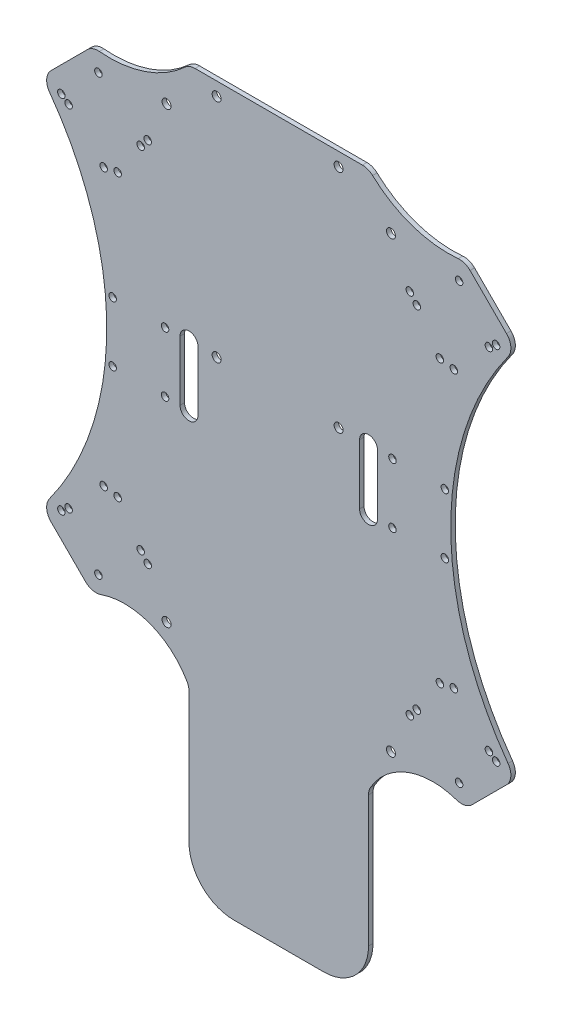
SolidWorks part; units mm, degrees
ref_plane "Front Plane" through (0, 0, 0) normal (0, 0, 1) x (1, 0, 0)
ref_plane "Top Plane" through (0, 0, 0) normal (0, 1, 0) x (1, 0, 0)
ref_plane "Right Plane" through (0, 0, 0) normal (1, 0, 0) x (0, 0, -1)
sketch "Sketch2" plane through (0, 0, 0) normal (0, 0, 1) x (1, 0, 0)
  line L0 (0, 0) -> (0, 50000) construction
  line L1 (0, 0) -> (35355.3391, 35355.3391) construction
  line L2 (0, 0) -> (35355.3391, -35355.3391) construction
  line L3 (-79.196, 62.2254) -> (-62.2254, 79.196)
  line L4 (0, 0) -> (-50000, 0) construction
  line L5 (-79.196, -62.2254) -> (-62.2254, -79.196)
  line L6 (30, 90) -> (-30, 90)
  line L7 (30, -90) -> (30, -135)
  line L8 (79.196, -62.2254) -> (62.2254, -79.196)
  line L9 (-30, -90) -> (-30, -135)
  line L10 (-15, -150) -> (15, -150)
  line L11 (79.196, 62.2254) -> (62.2254, 79.196)
  line L12 (-30, -90) -> (30, -150) construction
  line L13 (-30, -150) -> (30, -90) construction
  line L14 (30, -10) -> (30, 10) construction
  line L15 (27, -10) -> (27, 10)
  line L16 (33, -10) -> (33, 10)
  line L17 (-30, -10) -> (-30, 10) construction
  line L18 (-27, -10) -> (-27, 10)
  line L19 (-33, -10) -> (-33, 10)
  arc A0 (-79.196, 62.2254) -> (-79.196, -62.2254) centre (-157.4775, 0) cw
  arc A1 (-62.2254, 79.196) -> (-30, 90) centre (-56.6326, 115.976) ccw
  arc A2 (-62.2254, -79.196) -> (-30, -90) centre (-51.5147, -100.7107) cw
  arc A3 (15, -150) -> (30, -135) centre (15, -135) ccw
  arc A4 (-15, -150) -> (-30, -135) centre (-15, -135) cw
  arc A5 (62.2254, -79.196) -> (30, -90) centre (51.5147, -100.7107) ccw
  arc A6 (79.196, 62.2254) -> (79.196, -62.2254) centre (157.4775, 0) ccw
  arc A7 (62.2254, 79.196) -> (30, 90) centre (56.6326, 115.976) cw
  circle A8 centre (-37.5, 75) radius 1.5
  circle A9 centre (37.5, 75) radius 1.5
  circle A10 centre (37.5, -75) radius 1.5
  circle A11 centre (-37.5, -75) radius 1.5
  arc A12 (27, -10) -> (33, -10) centre (30, -10) ccw
  arc A13 (33, 10) -> (27, 10) centre (30, 10) ccw
  arc A14 (-27, -10) -> (-33, -10) centre (-30, -10) cw
  arc A15 (-33, 10) -> (-27, 10) centre (-30, 10) cw
  circle A16 centre (-55.5, 10) radius 1.25
  circle A17 centre (-38, 10) radius 1.25
  circle A18 centre (-55.5, -10) radius 1.25
  circle A19 centre (-38, -10) radius 1.25
  circle A20 centre (55.5, -10) radius 1.25
  circle A21 centre (38, -10) radius 1.25
  circle A22 centre (38, 10) radius 1.25
  circle A23 centre (55.5, 10) radius 1.25
  point P16 (-70.7107, 70.7107)
  point P24 (0, -120)
  point P32 (0, -150)
  point P45 (0, 90)
  point P49 (30, 0)
  point P56 (-30, 0)
  dimension "D9" = 10
  dimension "D4" = 37.5
  dimension "D8" = 30
  dimension "D17" = 2.5
  dimension "D1" = 150
  dimension "D2" = 45
  dimension "D3" = 45
  dimension "D5" = 30
  dimension "D6" = 60
  dimension "D7" = 75
  dimension "D10" = 10
  dimension "D11" = 10
  dimension "D12" = 10
  dimension "D13" = 17.5
  dimension "D14" = 17.5
  dimension "D15" = 38
  dimension "D16" = 38
extrude "Boss-Extrude1" add sketch "Sketch2" along normal blind 1.5
sketch "Sketch3" plane through (0, 0, 1.5) normal (0, 0, 1) x (1, 0, 0)
  line L0 (-70.7107, 70.7107) -> (35284.6284, -35284.6284) construction
  line L1 (-79.196, 62.2254) -> (-62.2254, 79.196) construction
  line L2 (0, 90) -> (0, 50090) construction
  line L3 (30, 90) -> (-30, 90) construction
  line L4 (70.7107, 70.7107) -> (35426.0497, 35426.0497) construction
  line L5 (79.196, 62.2254) -> (62.2254, 79.196) construction
  line L6 (0, 0) -> (50000, 0) construction
  circle A0 centre (-72.6552, 60.2809) radius 1.25
  circle A1 centre (-58.5131, 46.1387) radius 1.25
  circle A2 centre (-60.2809, 72.6552) radius 1.25
  circle A3 centre (-46.1387, 58.5131) radius 1.25
  circle A4 centre (58.5131, 46.1387) radius 1.25
  circle A5 centre (72.6552, 60.2809) radius 1.25
  circle A6 centre (60.2809, 72.6552) radius 1.25
  circle A7 centre (46.1387, 58.5131) radius 1.25
  circle A8 centre (-58.5131, -46.1387) radius 1.25
  circle A9 centre (-46.1387, -58.5131) radius 1.25
  circle A10 centre (-60.2809, -72.6552) radius 1.25
  circle A11 centre (-72.6552, -60.2809) radius 1.25
  circle A12 centre (58.5131, -46.1387) radius 1.25
  circle A13 centre (72.6552, -60.2809) radius 1.25
  circle A14 centre (60.2809, -72.6552) radius 1.25
  circle A15 centre (46.1387, -58.5131) radius 1.25
  point P6 (-70.7107, 70.7107)
  point P17 (0, 90)
  point P30 (70.7107, 70.7107)
  dimension "D1" = 8.75
  dimension "D3" = 8.75
  dimension "D2" = 6
  dimension "D4" = 20
  dimension "D5" = 6
extrude "45 Degrees" cut sketch "Sketch3" against normal through all
sketch "Sketch4" plane through (0, 0, 1.5) normal (0, 0, 1) x (1, 0, 0)
  line L0 (30, -90) -> (30, -135) construction
  line L1 (-20.76, 85.5) -> (20, 85.5)
  line L2 (-20.76, 85.5) -> (-20.76, 10)
  line L3 (-20.76, 10) -> (20, 10)
  line L4 (20, 85.5) -> (20, 10)
  line L5 (-15, -150) -> (15, -150) construction
  circle A0 centre (-20.76, 10) radius 1.5
  circle A1 centre (20, 10) radius 1.5
  circle A2 centre (-20.76, 85.5) radius 1.5
  circle A3 centre (20, 85.5) radius 1.5
  dimension "D1" = 75.5
  dimension "D2" = 40.76
  dimension "D3" = 10
  dimension "D4" = 160
extrude "ODroid holes" cut sketch "Sketch4" against normal through all contours A2 | A3 | A1 | A0
fillet "Fillet1" radius 5 1 edges at (-30, -90, 0.75)
fillet "Fillet2" radius 5 1 edges at (-62.2254, -79.196, 0.75)
fillet "Fillet3" radius 5 1 edges at (30, -90, 0.75)
fillet "Fillet4" radius 5 1 edges at (62.2254, -79.196, 0.75)
fillet "Fillet5" radius 5 1 edges at (79.196, -62.2254, 0.75)
fillet "Fillet6" radius 5 1 edges at (-79.196, -62.2254, 0.75)
fillet "Fillet7" radius 5 1 edges at (-79.196, 62.2254, 0.75)
fillet "Fillet8" radius 5 1 edges at (-62.2254, 79.196, 0.75)
fillet "Fillet9" radius 5 1 edges at (-30, 90, 0.75)
fillet "Fillet10" radius 5 1 edges at (30, 90, 0.75)
fillet "Fillet11" radius 5 1 edges at (62.2254, 79.196, 0.75)
fillet "Fillet12" radius 5 1 edges at (79.196, 62.2254, 0.75)
sketch "Sketch5" plane through (0, 0, 1.5) normal (0, 0, 1) x (1, 0, 0)
  line L0 (-60.1813, 72.7975) -> (28618.6406, 41030.3997) construction
  line L1 (-66.0068, 66.1947) -> (40891.5955, -28612.6271) construction
  line L2 (0, 0) -> (0, 50000) construction
  line L3 (0, 0) -> (50000, 0) construction
  circle A1 centre (-60.2809, 72.6552) radius 1.25
  circle A2 centre (-70.2188, 58.4623) radius 1.25
  circle A3 centre (-53.8358, 46.9908) radius 1.25
  circle A4 centre (-43.7988, 61.3264) radius 1.25
  circle A5 centre (60.2809, 72.6552) radius 1.25
  circle A6 centre (43.7988, 61.3264) radius 1.25
  circle A7 centre (53.8358, 46.9908) radius 1.25
  circle A8 centre (70.2188, 58.4623) radius 1.25
  circle A9 centre (-70.2188, -58.4623) radius 1.25
  circle A10 centre (-60.2809, -72.6552) radius 1.25
  circle A11 centre (-53.8358, -46.9908) radius 1.25
  circle A12 centre (-43.7988, -61.3264) radius 1.25
  circle A13 centre (70.2188, -58.4623) radius 1.25
  circle A14 centre (60.2809, -72.6552) radius 1.25
  circle A15 centre (43.7988, -61.3264) radius 1.25
  circle A16 centre (53.8358, -46.9908) radius 1.25
  dimension "D1" = 20
  dimension "D2" = 20
  dimension "D3" = 8.75
  dimension "D4" = 8.75
  dimension "D5" = 8.75
extrude "35 Degrees" cut sketch "Sketch5" against normal through all
